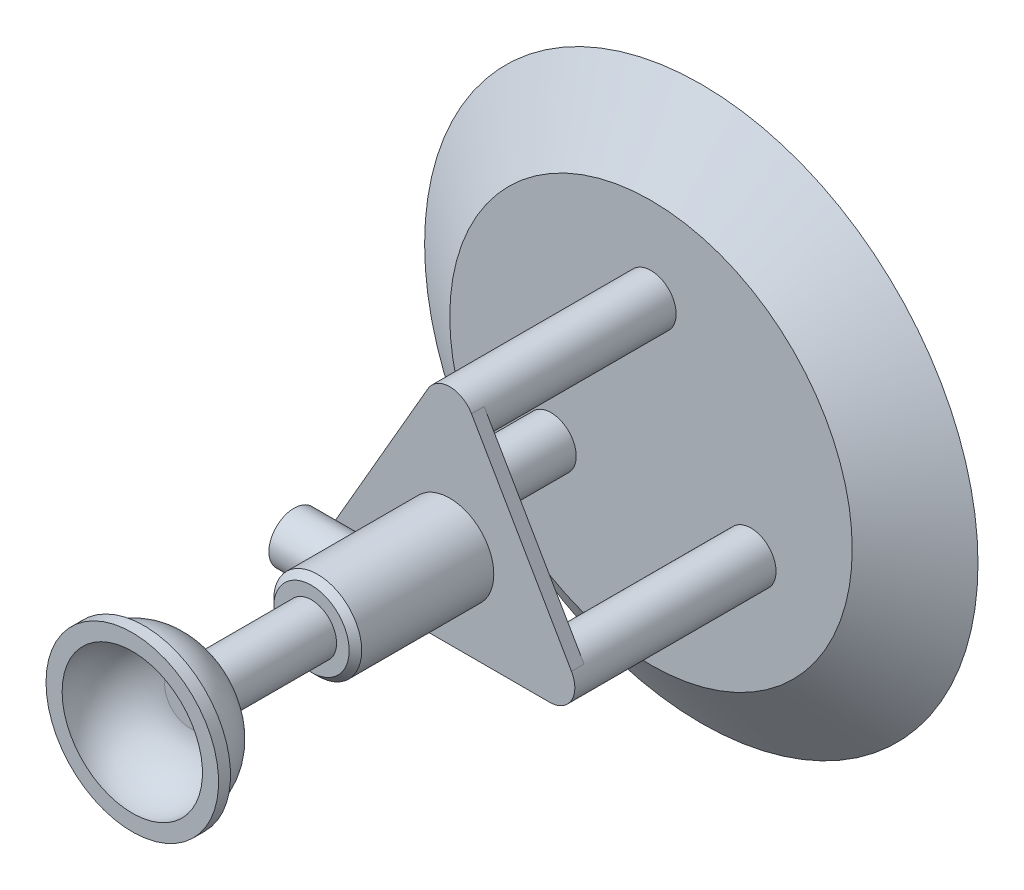
SolidWorks part; units mm, degrees
ref_plane "Alzado" through (0, 0, 0) normal (0, 0, 1) x (1, 0, 0)
ref_plane "Planta" through (0, 0, 0) normal (0, 1, 0) x (1, 0, 0)
ref_plane "Vista lateral" through (0, 0, 0) normal (1, 0, 0) x (0, 0, -1)
sketch "Sketch2" plane through (0, 0, 0) normal (1, 0, 0) x (0, 0, -1)
  line L0 (0, 0) -> (0, 22)
  line L1 (0, 22) -> (-4, 16)
  line L2 (-4, 16) -> (-4, 0)
  line L3 (-4, 0) -> (0, 0)
  dimension "D1" = 16
  dimension "D2" = 22
  dimension "D3" = 4
revolve "Revolve1" add sketch "Sketch2" angle 360 about L3
sketch "Sketch3" plane through (0, 0, 4) normal (0, 0, 1) x (1, 0, 0)
  circle A0 centre (7.9445, -4.5867) radius 2
  circle A1 centre (-7.9445, -4.5867) radius 2
  circle A2 centre (0, 9.1735) radius 2
  point P2 (0, 0)
  point P3 (0, 9.1735)
  point P8 (0, 0)
  dimension "D2" = 4
  dimension "D1" = 3
extrude "Boss-Extrude1" add sketch "Sketch3" along normal blind 15
sketch "Sketch4" plane through (0, 0, 19) normal (0, 0, 1) x (1, 0, 0)
  line L0 (1.7321, 10.1735) -> (9.6765, -3.5867)
  line L1 (-1.7321, 10.1735) -> (-9.6765, -3.5867)
  line L2 (7.9445, -6.5867) -> (-7.9445, -6.5867)
  circle A0 centre (-7.9445, -4.5867) radius 2 construction
  circle A1 centre (7.9445, -4.5867) radius 2
  arc A2 (7.9445, -6.5867) -> (9.6765, -3.5867) centre (7.9445, -4.5867) ccw
  circle A3 centre (0, 9.1735) radius 2 construction
  arc A4 (-9.6765, -3.5867) -> (-7.9445, -6.5867) centre (-7.9445, -4.5867) ccw
  arc A5 (1.7321, 10.1735) -> (-1.7321, 10.1735) centre (0, 9.1735) ccw
  dimension "D1" = 0
extrude "Boss-Extrude2" add sketch "Sketch4" along normal blind 1
sketch "Sketch6" plane through (0, 0, 20) normal (0, 0, 1) x (1, 0, 0)
  circle A0 centre (0, 0) radius 3.5
  dimension "D1" = 7
extrude "Boss-Extrude3" add sketch "Sketch6" along normal blind 11
sketch "Sketch7" plane through (0, 0, 31) normal (0, 0, 1) x (1, 0, 0)
  circle A0 centre (0, 0) radius 2
  dimension "D1" = 4
extrude "Boss-Extrude4" add sketch "Sketch7" along normal blind 9
chamfer "Chamfer2" distance 0.5 angle 45 1 edges at (3.5, 0, 31)
sketch "Sketch8" plane through (0, 0, 0) normal (0, 1, 0) x (1, 0, 0)
  line L0 (0, -40) -> (2, -40)
  line L1 (-2, -40) -> (2, -40) construction
  line L2 (6.1919, -44.2934) -> (6.8613, -44.2934)
  line L3 (6.8613, -44.2934) -> (6.8613, -45.2417)
  line L4 (6.8613, -45.2417) -> (5.5783, -45.2417)
  line L5 (0, -40) -> (0, -40.6675)
  line L6 (0, -40.6675) -> (2, -40.6675)
  arc A0 (2, -40) -> (6.1919, -44.2934) centre (1.9493, -44.2426) cw
  arc A1 (5.5783, -45.2417) -> (2, -40.6675) centre (1.502, -44.7437) ccw
revolve "Revolve2" add sketch "Sketch8" angle 360 about L5
sketch "Sketch9" plane through (0, 0, 0) normal (1, 0, 0) x (0, 0, -1)
  circle A0 centre (-25.3821, 0) radius 2
extrude "Boss-Extrude5" add sketch "Sketch9" against normal blind 7
